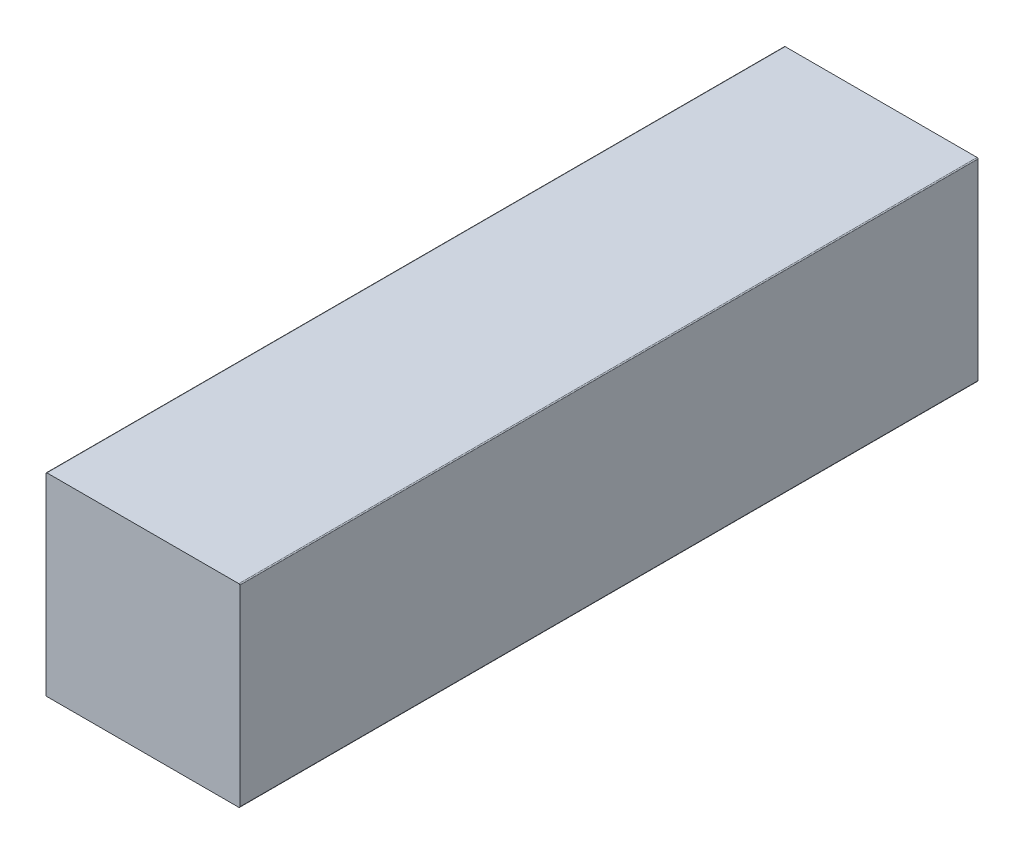
SolidWorks part; units mm, degrees
material "AISI 1045 Steel, cold drawn"
ref_plane "Front Plane" through (0, 0, 0) normal (0, 0, 1) x (1, 0, 0)
ref_plane "Top Plane" through (0, 0, 0) normal (0, 1, 0) x (1, 0, 0)
ref_plane "Right Plane" through (0, 0, 0) normal (1, 0, 0) x (0, 0, -1)
sketch "Sketch1" plane through (0, 0, 0) normal (0, 0, 1) x (1, 0, 0)
  line L1 (2.5, -2.5) -> (-2.5, -2.5)
  line L2 (2.5, -2.5) -> (2.5, 2.5)
  line L3 (2.5, 2.5) -> (-2.5, 2.5)
  line L4 (-2.5, -2.5) -> (-2.5, 2.5)
  line L5 (2.5, -2.5) -> (-2.5, 2.5) construction
  line L6 (2.5, 2.5) -> (-2.5, -2.5) construction
  point P0 (0, 0)
  dimension "Height" = 5
  dimension "Width" = 5
sketch "Sketch2" plane through (0, 0, 0) normal (1, 0, 0) x (0, 0, -1)
  line L0 (-153, 0) -> (153, 0) construction
  line L1 (0, 0) -> (0, 2.5) construction
  line L3 (-152.5, -2.5) -> (152.5, -2.5)
  line L4 (-152.5, -2.5) -> (-152.5, 2.5)
  line L5 (-152.5, 2.5) -> (152.5, 2.5)
  line L6 (152.5, -2.5) -> (152.5, 2.5)
  line L7 (0, 2.5) -> (0, -2.5) construction
  line L8 (-152.5, 0) -> (152.5, 0) construction
  point P0 (-152.5, 0)
  point P4 (0, 0)
  point P6 (152.5, 0)
  dimension "D1" = 0.5
  dimension "Length" = 305
sketch "Sketch3" plane through (0, 0, 0) normal (0, 0, 1) x (1, 0, 0)
  line L4 (-2.5, -2.5) -> (-2.5, 2.5)
  line L5 (2.5, -2.5) -> (-2.5, -2.5)
  line L6 (2.5, -2.5) -> (2.5, 2.5)
  line L7 (2.5, 2.5) -> (-2.5, 2.5)
  line L8 (0, -2.5) -> (0, 2.5) construction
  line L9 (2.5, 0) -> (-2.5, 0) construction
  point P8 (0, 0)
  dimension "Height" = 5
  dimension "Width" = 5
extrude "Boss-Extrude1" add sketch "Sketch3" along normal mid plane 305
fillet "Fillet1" radius 0.025 4 edges at (-2.5, -2.5, 0) (-2.5, 2.5, 0) (2.5, -2.5, 0) (2.5, 2.5, 0)
sketch "Sketch4" plane through (0, 0, 152.5) normal (0, 0, 1) x (1, 0, 0)
  line L0 (2.475, 2.5) -> (-2.475, 2.5) construction
  line L1 (-2.5, -2.5) -> (2.5, -2.5)
  line L2 (-2.5, -2.5) -> (-2.5, 2.5)
  line L3 (-2.5, 2.5) -> (2.5, 2.5)
  line L4 (2.5, -2.5) -> (2.5, 2.5)
  line L5 (-2.5, -2.5) -> (2.5, 2.5) construction
  line L6 (-2.5, 2.5) -> (2.5, -2.5) construction
  line L7 (2.5, -2.475) -> (2.5, 2.475) construction
  point P0 (0, 0)
extrude "Cut-Extrude1" cut sketch "Sketch4" against normal blind 285.95
equation "\"D1@Boss-Extrude1\"=\"Length@Sketch2\""
equation "\"Height@Sketch3\" = \"Height@Sketch1\""
equation "\"Width@Sketch3\" = \"Width@Sketch1\""
equation "\"D1@Fillet1\"=\"Width@Sketch1\"*.005"
